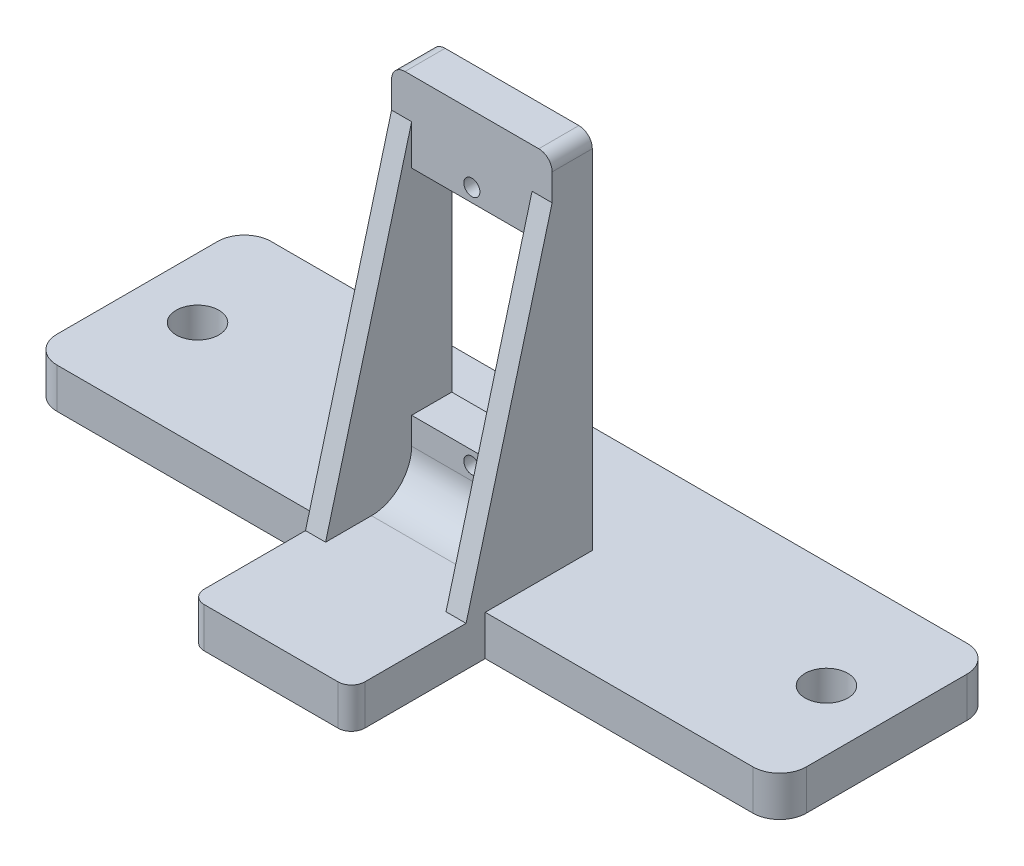
SolidWorks part; units mm, degrees
ref_plane "前视基准面" through (0, 0, 0) normal (0, 0, 1) x (1, 0, 0)
ref_plane "上视基准面" through (0, 0, 0) normal (0, 1, 0) x (1, 0, 0)
ref_plane "右视基准面" through (0, 0, 0) normal (1, 0, 0) x (0, 0, -1)
other "Configuration Table"
sketch "草图1" plane through (0, 0, 0) normal (0, 1, 0) x (1, 0, 0)
  line L1 (-28, -8) -> (28, -8)
  line L2 (-28, -8) -> (-28, 8)
  line L3 (-28, 8) -> (28, 8)
  line L4 (28, -8) -> (28, 8)
  line L5 (-28, -8) -> (28, 8) construction
  line L6 (-28, 8) -> (28, -8) construction
  point P0 (0, 0)
  dimension "D1" = 56
  dimension "D2" = 16
extrude "凸台-拉伸1" add sketch "草图1" along normal blind 3
sketch "草图2" plane through (0, 3, 0) normal (0, 1, 0) x (1, 0, 0)
  line L0 (28, 8) -> (-28, 8) construction
  line L1 (-3, 4.5) -> (13, 4.5)
  line L2 (-3, 4.5) -> (-3, 0.9)
  line L3 (-3, -4.5) -> (13, -4.5)
  line L4 (13, 4.5) -> (13, 0.9)
  line L5 (15, 0.9) -> (13, 0.9)
  line L6 (20.4591, 0) -> (-14.3659, 0) construction
  line L7 (5, -11.1413) -> (5, 15.0553) construction
  line L8 (15, -0.9) -> (13, -0.9)
  line L9 (13, -0.9) -> (13, -4.5)
  line L10 (-5, -0.9) -> (-3, -0.9)
  line L11 (-5, 0.9) -> (-3, 0.9)
  line L12 (-3, -0.9) -> (-3, -4.5)
  circle A0 centre (0, 0) radius 3.8087 construction
  arc A1 (15, -0.9) -> (15, 0.9) centre (15, 0) ccw
  arc A2 (-5, -0.9) -> (-5, 0.9) centre (-5, 0) cw
  point P16 (5, 4.5)
  dimension "D5" = 1.8
  dimension "D6" = 10
  dimension "D1" = 9
  dimension "D2" = 16
  dimension "D3" = 3.5
  dimension "D4" = 3
extrude "切除-拉伸1" [suppressed] cut sketch "草图2" against normal blind 5
sketch "草图3" plane through (0, 3, 0) normal (0, 1, 0) x (1, 0, 0)
  line L0 (-30.155, 0) -> (33.046, 0) construction
  line L1 (0, -13.9878) -> (0, 14.2992) construction
  circle A0 centre (23.5, 0) radius 1.6
  circle A1 centre (-23.5, 0) radius 1.6
  dimension "D1" = 3.2
  dimension "D2" = 23.5
  dimension "D3" = 23.5
  dimension "D4" = 3.2
extrude "切除-拉伸2" cut sketch "草图3" against normal blind 5
fillet "圆角1" radius 2 4 edges at (28, 1.5, -8) (28, 1.5, 8) (-28, 1.5, 8) (-28, 1.5, -8)
sketch "草图4" plane through (0, 3, 0) normal (0, 1, 0) x (1, 0, 0)
  line L0 (0, -18) -> (0, 17.7683) construction
  line L1 (6, 0) -> (-6, 0)
  line L2 (-6, 0) -> (-6, -17)
  line L3 (-5, -18) -> (5, -18)
  line L4 (6, 0) -> (6, -17)
  line L5 (6, -8) -> (-6, -8)
  line L6 (-26, -8) -> (26, -8) construction
  arc A0 (6, -17) -> (5, -18) centre (5, -17) cw
  arc A1 (-6, -17) -> (-5, -18) centre (-5, -17) ccw
  point P8 (0, 0)
  point P14 (6, -18)
  point P17 (-6, -18)
  line M14 (-26, -8) -> (26, -8)
  dimension "D3" = 1
  dimension "D1" = 6
  dimension "D2" = 18
extrude "凸台-拉伸2" add sketch "草图4" against normal up to surface (3 mm away) contours L0 L3 A0 L4 L5 | L3 L0 L2 A1 M14 up to face at (23.5, 0, -1.6)
sketch "草图5" plane through (0, 0, 0) normal (0, 0, 1) x (1, 0, 0)
  line L0 (0, -10.0416) -> (0, 25.1677) construction
  line L1 (-6, 3) -> (-6, 29)
  line L2 (-5, 30) -> (5, 30)
  line L3 (6, 3) -> (6, 29)
  line L4 (-6, 3) -> (6, 3)
  line L5 (13.5208, 16) -> (-12.9871, 16) construction
  line L6 (-4.5, 8) -> (4.5, 8)
  line L7 (-4.5, 8) -> (-4.5, 24)
  line L8 (-4.5, 24) -> (4.5, 24)
  line L9 (4.5, 8) -> (4.5, 24)
  line L10 (-4.5, 8) -> (4.5, 24) construction
  line L11 (-4.5, 24) -> (4.5, 8) construction
  arc A0 (6, 29) -> (5, 30) centre (5, 29) ccw
  arc A1 (-6, 29) -> (-5, 30) centre (-5, 29) cw
  circle A2 centre (0, 7) radius 0.6
  circle A3 centre (0, 25) radius 0.6
  point P9 (0, 30)
  point P11 (6, 30)
  point P14 (-6, 30)
  point P15 (0, 16)
  dimension "D2" = 1
  dimension "D6" = 1.2
  dimension "D7" = 18
  dimension "D1" = 27
  dimension "D3" = 16
  dimension "D4" = 9
  dimension "D5" = 6
extrude "凸台-拉伸3" add sketch "草图5" along normal blind 3
sketch "草图7" plane through (6, 0, 0) normal (1, 0, 0) x (0, 0, -1)
  line L0 (-3, 27) -> (-9.4308, 3)
  line L1 (-3, 3) -> (-3, 29) construction
  line L2 (-8, 3) -> (-17, 3) construction
  line L3 (-6, 3) -> (6, 3) construction
  line L4 (-3, 27) -> (-3, 3)
  line L5 (-3, 3) -> (-9.4308, 3)
  dimension "D1" = 15
  dimension "D2" = 24
extrude "凸台-拉伸5" add sketch "草图7" against normal up to surface (1.5 mm away) up to face at (4.5, 16, 1.5)
sketch "草图8" plane through (-6, 0, 0) normal (-1, 0, 0) x (0, 0, 1)
  line L0 (3, 27) -> (9.4308, 3) construction
  line L1 (3, 27) -> (9.4308, 3)
  line L2 (3, 27) -> (3, 3)
  line L3 (3, 3) -> (9.4308, 3)
extrude "凸台-拉伸6" add sketch "草图8" against normal up to surface (1.5 mm away) up to face at (-4.5, 16, 1.5)
sketch "草图9" plane through (4.5, 0, 0) normal (-1, 0, 0) x (0, 0, 1)
  line L0 (3, 29) -> (3, 27) construction
  line L1 (9.4308, 3) -> (17, 3) construction
  line L2 (3, 6) -> (3, 3)
  line L3 (3, 3) -> (6, 3)
  arc A0 (3, 6) -> (6, 3) centre (6, 6) ccw
  dimension "D1" = 6
extrude "凸台-拉伸7" add sketch "草图9" along normal up to surface (9 mm away) up to face at (-4.5, 13.8571, 3.0615)
